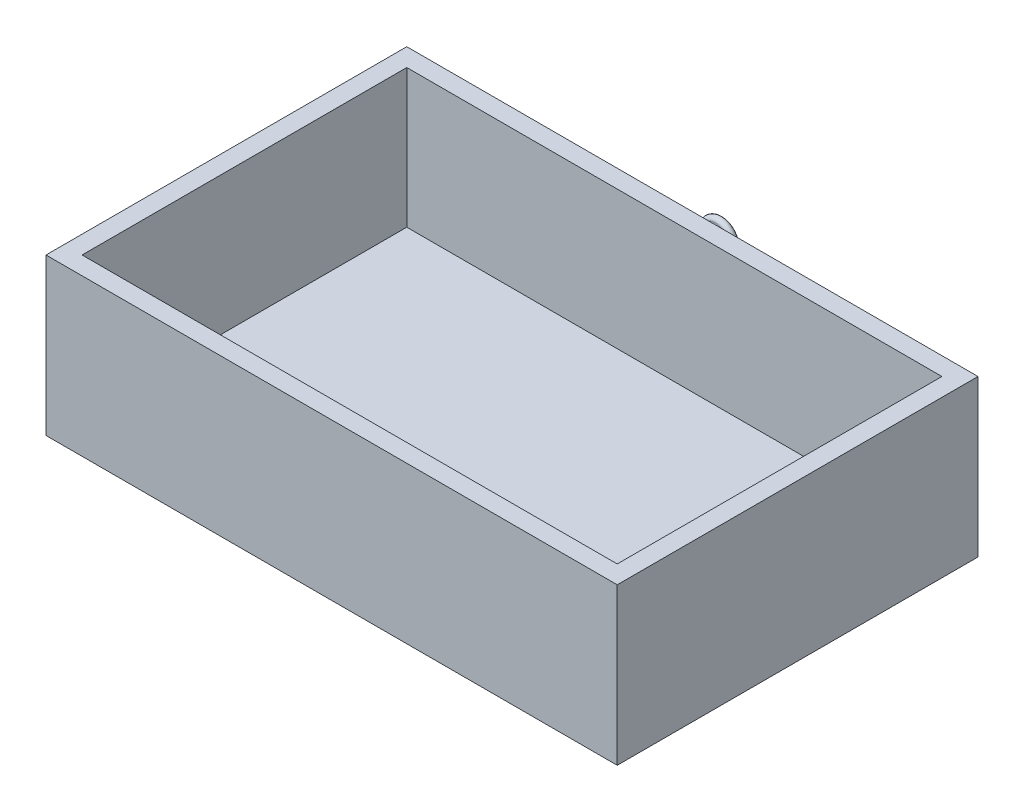
SolidWorks part; units mm, degrees
ref_plane "Front Plane" through (0, 0, 0) normal (0, 0, 1) x (1, 0, 0)
ref_plane "Top Plane" through (0, 0, 0) normal (0, 1, 0) x (1, 0, 0)
ref_plane "Right Plane" through (0, 0, 0) normal (1, 0, 0) x (0, 0, -1)
sketch "Sketch1" plane through (0, 0, 0) normal (0, 0, 1) x (1, 0, 0)
  line L0 (-50.5556, 119.7444) -> (424.4444, 119.7444)
  line L1 (424.4444, 119.7444) -> (424.4444, -10.2556)
  line L2 (424.4444, -10.2556) -> (-50.5556, -10.2556)
  line L3 (-50.5556, -10.2556) -> (-50.5556, 119.7444)
  dimension "D1" = 475
  dimension "D2" = 130
extrude "Boss-Extrude1" add sketch "Sketch1" along normal blind 300
shell "Shell1" thickness 15
ref_plane "Plane1" through (186.9444, 0, 0) normal (-1, 0, 0) x (0, 0, 1)
sketch "Sketch3" plane through (186.9444, 0, 0) normal (-1, 0, 0) x (0, 0, 1)
  line L6 (0, 89.7444) -> (-25, 89.7444)
  line L8 (-25, 89.7444) -> (-25, 102.1147)
  line L9 (-14, 97.1147) -> (0, 97.1147)
  line L10 (0, 97.1147) -> (0, 89.7444)
  arc A2 (-25, 102.1147) -> (-19, 102.1147) centre (-22, 102.1147) cw
  arc A3 (-19, 102.1147) -> (-14, 97.1147) centre (-14, 102.1147) ccw
  point P0 (0, 0)
  dimension "D5" = 5
  dimension "D6" = 3
  dimension "D7" = 25
revolve "Revolve2" add sketch "Sketch3" angle 360 about L6
